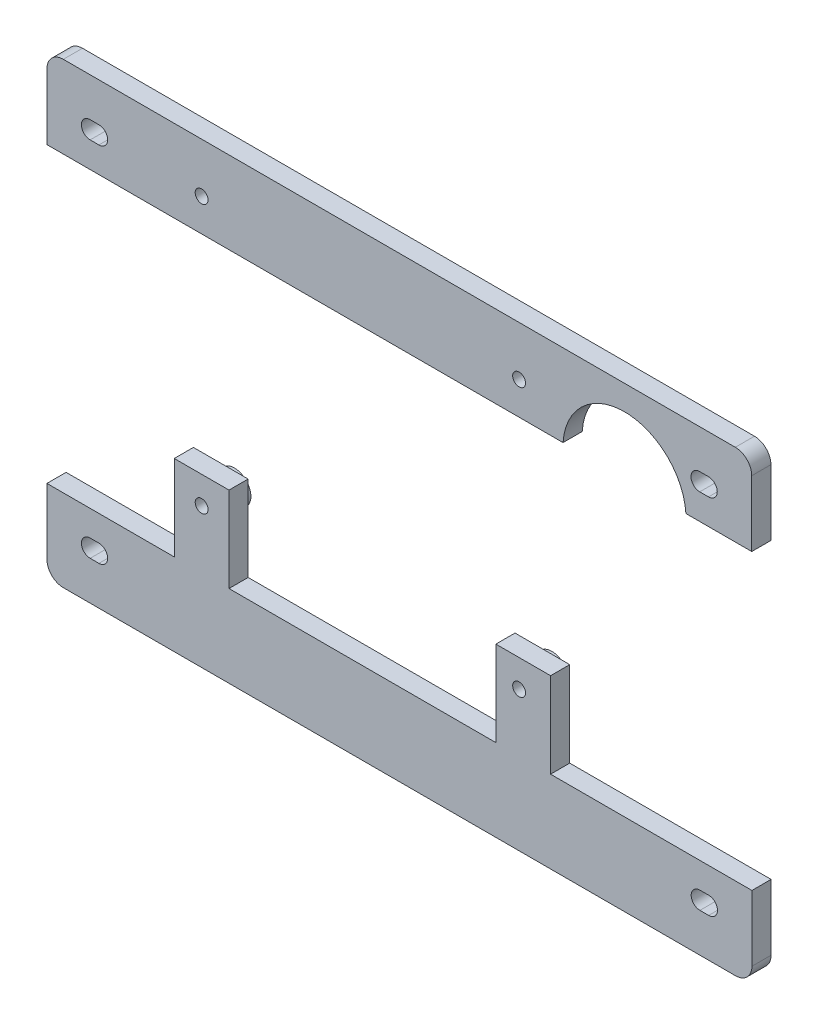
SolidWorks part; units mm, degrees
ref_plane "Płaszczyzna przednia" through (0, 0, 0) normal (0, 0, 1) x (1, 0, 0)
ref_plane "Płaszczyzna górna" through (0, 0, 0) normal (0, 1, 0) x (1, 0, 0)
ref_plane "Płaszczyzna prawa" through (0, 0, 0) normal (1, 0, 0) x (0, 0, -1)
sketch "Szkic1" plane through (0, 0, 0) normal (0, 0, 1) x (1, 0, 0)
  line L0 (-82.1865, -22.5201) -> (46.6135, -22.5201)
  line L3 (-82.1865, -37.5201) -> (46.6135, -37.5201)
  line L6 (-82.1865, -22.5201) -> (-82.1865, -37.5201)
  line L7 (46.6135, -22.5201) -> (46.6135, -37.5201)
  dimension "D4" = 15
extrude "Dodanie-wyciągnięcie1" add sketch "Szkic1" along normal blind 3.5
sketch "Szkic2" plane through (0, 0, 3.5) normal (0, 0, 1) x (1, 0, 0)
  line L0 (-82.1865, -37.5201) -> (46.6135, -37.5201) construction
  line L1 (-82.1865, 31.0799) -> (46.5789, 31.0799)
  line L3 (-82.1865, 46.0799) -> (46.5789, 46.0799)
  line L5 (-82.1865, 31.0799) -> (-82.1865, 46.0799)
  line L6 (46.5789, 31.0799) -> (46.5789, 46.0799)
  dimension "D2" = 83.6
extrude "Dodanie-wyciągnięcie2" add sketch "Szkic2" against normal up to surface (3.5 mm away) separate body up to face at (-17.7865, -30.0201, 0)
sketch "Szkic3" plane through (0, 0, 0) normal (0, 0, -1) x (-1, 0, 0)
  line L0 (-46.6135, -37.5201) -> (-46.6135, -22.5201) construction
  line L1 (-46.5789, 46.0799) -> (-46.5789, 31.0799) construction
  line L2 (82.1865, -22.5201) -> (82.1865, -37.5201) construction
  line L3 (82.1865, 31.0799) -> (82.1865, 46.0799) construction
  line L4 (82.1865, 46.0799) -> (-46.5789, 46.0799) construction
  line L5 (82.1865, -37.5201) -> (-46.6135, -37.5201) construction
  circle A0 centre (-37.1135, -28.8201) radius 1.6
  circle A1 centre (-37.0789, 37.3799) radius 1.6
  circle A2 centre (72.6865, -28.8201) radius 1.6
  circle A3 centre (72.6865, 37.3799) radius 1.6
  dimension "D5" = 3.2
  dimension "D6" = 3.2
  dimension "D7" = 3.2
  dimension "D8" = 3.2
  dimension "D1" = 9.5
  dimension "D2" = 9.5
  dimension "D3" = 9.5
  dimension "D4" = 9.5
  dimension "D9" = 8.7
  dimension "D10" = 8.7
  dimension "D11" = 8.7
  dimension "D12" = 8.7
extrude "Wytnij-wyciągnięcie1" cut sketch "Szkic3" against normal through all
sketch "Szkic4" plane through (0, 0, 3.5) normal (0, 0, 1) x (1, 0, 0)
  line L0 (46.5789, 31.0799) -> (46.5789, 46.0799) construction
  line L1 (46.5789, 46.0799) -> (-82.1865, 46.0799) construction
  circle A0 centre (23.3289, 30.3299) radius 11.25
  dimension "D1" = 23.25
  dimension "D2" = 15.75
extrude "Wytnij-wyciągnięcie2" cut sketch "Szkic4" against normal blind 10
sketch "Szkic5" plane through (0, 0, 3.5) normal (0, 0, 1) x (1, 0, 0)
  circle A0 centre (4.0794, 37.0568) radius 1.9995 construction
  circle A1 centre (4.0794, 37.0568) radius 3
  circle A2 centre (-53.9206, 37.0354) radius 1.9785 construction
  circle A3 centre (-53.9206, 37.0354) radius 3
  circle A4 centre (-53.9203, -11.9496) radius 1.9948 construction
  circle A5 centre (-53.9203, -11.9496) radius 3
  circle A6 centre (4.0794, -11.9612) radius 1.9838 construction
  circle A7 centre (4.0794, -11.9612) radius 3
  dimension "D1" = 58
extrude "Dodanie-wyciągnięcie3" add sketch "Szkic5" against normal blind 6
fillet "Zaokrąglenie1" radius 3 1 edges at (-82.1865, -37.5201, 1.75)
fillet "Zaokrąglenie2" radius 3 1 edges at (-82.1865, 46.0799, 1.75)
fillet "Zaokrąglenie3" radius 3 1 edges at (46.5789, 46.0799, 1.75)
fillet "Zaokrąglenie4" radius 3 1 edges at (46.6135, -37.5201, 1.75)
sketch "Szkic7" plane through (0, 0, 3.5) normal (0, 0, 1) x (1, 0, 0)
  line L1 (9.8302, -28.6422) -> (-0.1698, -28.6422)
  line L2 (9.8302, -28.6422) -> (9.8302, -6.9354)
  line L3 (9.8302, -6.9354) -> (-0.1698, -6.9354)
  line L4 (-0.1698, -28.6422) -> (-0.1698, -6.9354)
  line L5 (-48.9228, -26.7101) -> (-58.9228, -26.7101)
  line L6 (-48.9228, -26.7101) -> (-48.9228, -6.9425)
  line L7 (-48.9228, -6.9425) -> (-58.9228, -6.9425)
  line L8 (-58.9228, -26.7101) -> (-58.9228, -6.9425)
  circle A1 centre (-53.9228, -11.9425) radius 2.003 construction
  dimension "D2" = 10
  dimension "D4" = 10
  dimension "D5" = 5
  dimension "D6" = 5
extrude "Dodanie-wyciągnięcie4" add sketch "Szkic7" against normal up to surface (3.5 mm away) up to face at (35.5135, -28.8201, 0)
sketch "Szkic8" plane through (0, 0, -2.5) normal (0, 0, -1) x (-1, 0, 0)
  circle A0 centre (-4.0794, -11.9612) radius 1.175
  circle A1 centre (53.9203, -11.9496) radius 1.175
  circle A2 centre (53.9206, 37.0354) radius 1.175
  circle A3 centre (-4.0794, 37.0568) radius 1.175
  dimension "D1" = 58
  dimension "D2" = 2.35
  dimension "D3" = 2.35
  dimension "D4" = 2.35
  dimension "D5" = 2.35
extrude "Wytnij-wyciągnięcie4" cut sketch "Szkic8" against normal through all
sketch "Szkic9" plane through (0, 0, 0) normal (0, 0, -1) x (-1, 0, 0)
  line L1 (74.2865, 35.7799) -> (72.6865, 35.7799)
  line L3 (74.2865, 38.9799) -> (72.6865, 38.9799)
  line L4 (72.6865, 35.7799) -> (72.6865, 38.9799)
  line L5 (-38.6789, 35.7799) -> (-37.0789, 35.7799)
  line L7 (-38.6789, 38.9799) -> (-37.0789, 38.9799)
  line L8 (-37.0789, 35.7799) -> (-37.0789, 38.9799)
  line L9 (-38.7135, -30.4201) -> (-37.1135, -30.4201)
  line L11 (-38.7135, -27.2201) -> (-37.1135, -27.2201)
  line L12 (-37.1135, -30.4201) -> (-37.1135, -27.2201)
  line L13 (74.2865, -30.4201) -> (72.6865, -30.4201)
  line L15 (74.2865, -27.2201) -> (72.6865, -27.2201)
  line L16 (72.6865, -30.4201) -> (72.6865, -27.2201)
  arc A0 (74.2865, -30.4201) -> (74.2865, -27.2201) centre (74.2865, -28.8201) ccw
  circle A1 centre (72.6865, -28.8201) radius 1.6 construction
  arc A2 (-38.7135, -27.2201) -> (-38.7135, -30.4201) centre (-38.7135, -28.8201) ccw
  circle A3 centre (-37.1135, -28.8201) radius 1.6 construction
  arc A4 (-38.6789, 38.9799) -> (-38.6789, 35.7799) centre (-38.6789, 37.3799) ccw
  circle A5 centre (-37.0789, 37.3799) radius 1.6 construction
  arc A6 (74.2865, 35.7799) -> (74.2865, 38.9799) centre (74.2865, 37.3799) ccw
  circle A7 centre (72.6865, 37.3799) radius 1.6 construction
extrude "Wytnij-wyciągnięcie5" cut sketch "Szkic9" against normal through all
